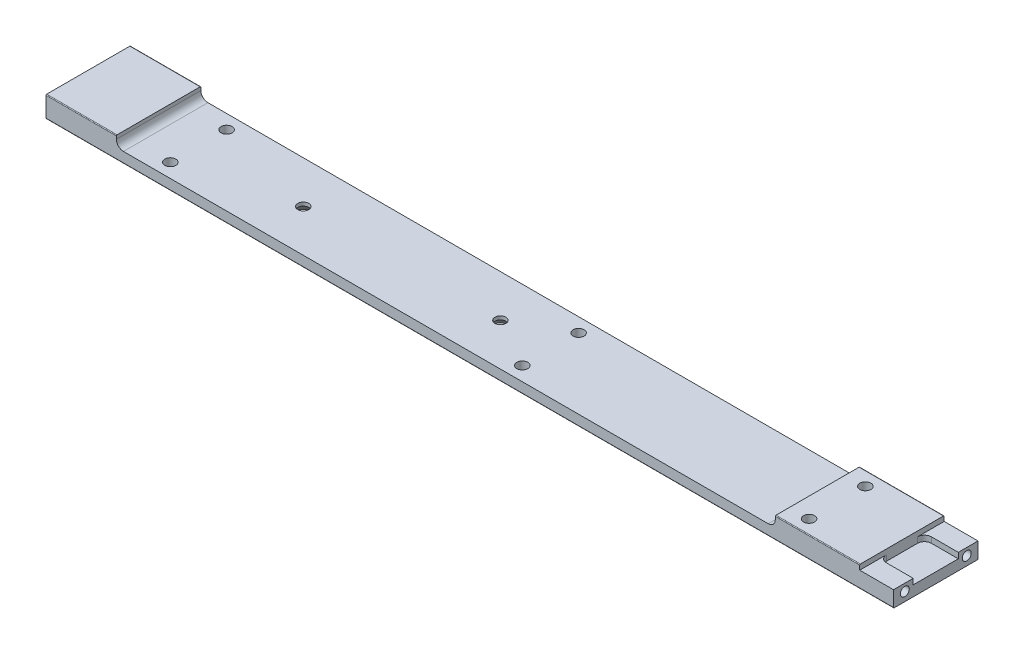
SolidWorks part; units mm, degrees
material "6061 Alloy"
ref_plane "Front Plane" through (0, 0, 0) normal (0, 0, 1) x (1, 0, 0)
ref_plane "Top Plane" through (0, 0, 0) normal (0, 1, 0) x (1, 0, 0)
ref_plane "Right Plane" through (0, 0, 0) normal (1, 0, 0) x (0, 0, -1)
sketch "Sketch1" plane through (0, 0, 0) normal (0, 1, 0) x (1, 0, 0)
  line L1 (191.135, -19.05) -> (-191.135, -19.05)
  line L2 (191.135, -19.05) -> (191.135, 19.05)
  line L3 (191.135, 19.05) -> (-191.135, 19.05)
  line L4 (-191.135, -19.05) -> (-191.135, 19.05)
  line L5 (191.135, -19.05) -> (-191.135, 19.05) construction
  line L6 (191.135, 19.05) -> (-191.135, -19.05) construction
  point P0 (0, 0)
  dimension "Length" = 382.27
  dimension "Width" = 38.1
sketch "Sketch2" plane through (0, 0, 0) normal (1, 0, 0) x (0, 0, -1)
  line L0 (19.05, 4.7625) -> (19.05, -4.7625) construction
  point P2 (19.05, 0)
  dimension "Thickness" = 9.525
sketch "Sketch3" plane through (0, 0, 0) normal (0, 1, 0) x (1, 0, 0)
  line L1 (-191.135, 19.05) -> (191.135, 19.05)
  line L2 (-191.135, 19.05) -> (-191.135, -19.05)
  line L3 (-191.135, -19.05) -> (191.135, -19.05)
  line L4 (191.135, 19.05) -> (191.135, -19.05)
extrude "Boss-Extrude1" add sketch "Sketch3" against normal up to vertex (4.7625 mm away) and the other way up to vertex (4.7625 mm away) up to point (0, -4.7625, -19.05) other way up to point (0, 4.7625, -19.05)
fillet "Fillet1" radius 0.3143 4 edges at (0, -4.7625, 19.05) (0, -4.7625, -19.05) (0, 4.7625, -19.05) (0, 4.7625, 19.05)
sketch "Sketch4" plane through (-191.135, 0, 0) normal (-1, 0, 0) x (0, 0, 1)
  line L0 (0, -0.762) -> (13.97, -0.762) construction
  line L1 (0, -0.762) -> (-13.97, -0.762) construction
  line L2 (0, -0.762) -> (0, 0) construction
  dimension "D1" = 13.97
  dimension "D2" = 13.97
  dimension "D3" = 0.762
hole_wizard "Tap Drill for #10-32 Tap1" positions "Sketch5" profile "Sketch6" hole size "#10-32" standard "ANSI Inch"
sketch "Sketch5" plane through (-191.135, 0, 0) normal (-1, 0, 0) x (0, 0, 1)
  point P0 (-13.97, -0.762)
  point P3 (13.97, -0.762)
sketch "Sketch6" plane through (-191.135, -0.762, -13.97) normal (0, 1, 0) x (0, 0, 1)
  line L0 (0, 0) -> (0, 26.6133)
  line L1 (0, 26.6133) -> (2.0193, 25.4)
  line L2 (2.0193, 25.4) -> (2.0193, 0)
  line L5 (2.0193, 0) -> (0, 0)
  line L10 (0, 26.6133) -> (-2.0193, 25.4) construction
  line L11 (0, -6.35) -> (0, 107.95) construction
  dimension "Hole Dia." = 4.0386
  dimension "Hole Depth" = 25.4
  dimension "Drill Angle" = 118
hole_wizard "Tap Drill for #10-32 Tap2" positions "Sketch7" profile "Sketch8" hole size "#10-32" standard "ANSI Inch"
sketch "Sketch7" plane through (191.135, 0, 0) normal (1, 0, 0) x (0, 0, -1)
  point P0 (-13.97, -0.762)
  point P3 (13.97, -0.762)
sketch "Sketch8" plane through (191.135, -0.762, 13.97) normal (0, 1, 0) x (0, 0, -1)
  line L0 (0, 0) -> (0, 26.6133)
  line L1 (0, 26.6133) -> (2.0193, 25.4)
  line L2 (2.0193, 25.4) -> (2.0193, 0)
  line L5 (2.0193, 0) -> (0, 0)
  line L10 (0, 26.6133) -> (-2.0193, 25.4) construction
  line L11 (0, -6.35) -> (0, 107.95) construction
  dimension "Hole Dia." = 4.0386
  dimension "Hole Depth" = 25.4
  dimension "Drill Angle" = 118
sketch "Sketch10" plane through (0, 0, -19.05) normal (0, 0, -1) x (-1, 0, 0)
  line L0 (159.385, 4.7625) -> (159.385, 3.175)
  line L1 (-191.135, 4.7625) -> (191.135, 4.7625) construction
  line L2 (156.21, 0) -> (-134.62, 0)
  line L3 (-137.795, 3.175) -> (-137.795, 4.7625)
  line L4 (-137.795, 4.7625) -> (159.385, 4.7625)
  line L5 (-191.135, -3.175) -> (-191.135, 33.0219) construction
  line L6 (191.135, -3.175) -> (191.135, 33.0219) construction
  line L7 (-191.135, 4.7625) -> (-175.895, 4.7625)
  line L8 (-175.895, 4.7625) -> (-175.895, 2.4765)
  line L9 (-175.895, 2.4765) -> (-191.135, 2.4765)
  line L10 (-191.135, -4.4482) -> (-191.135, 4.4482) construction
  line L11 (-191.135, 2.4765) -> (-191.135, 4.7625)
  arc A0 (159.385, 3.175) -> (156.21, 0) centre (156.21, 3.175) cw
  arc A1 (-134.62, 0) -> (-137.795, 3.175) centre (-134.62, 3.175) cw
  point P12 (159.385, 0)
  dimension "D4" = 3.175
  dimension "D1" = 53.34
  dimension "D2" = 31.75
  dimension "D3" = 4.7625
  dimension "D5" = 15.24
  dimension "D6" = 2.286
extrude "Cut-Extrude1" cut sketch "Sketch10" against normal through all
sketch "Sketch13" plane through (0, -4.7625, 0) normal (0, -1, 0) x (1, 0, 0)
  line L0 (191.135, 0) -> (146.685, 0) construction
  line L1 (191.135, 18.7357) -> (191.135, -18.7357) construction
  line L2 (146.685, 0) -> (146.685, 12.7) construction
  line L3 (146.685, 12.7) -> (114.935, 12.7) construction
  line L4 (114.935, 12.7) -> (114.935, -12.7) construction
  line L5 (114.935, -12.7) -> (146.685, -12.7) construction
  line L6 (146.685, -12.7) -> (146.685, 0) construction
  dimension "D1" = 44.45
  dimension "D2" = 31.75
  dimension "D3" = 31.75
hole_wizard "#10 Clearance Hole1" positions "Sketch14" profile "Sketch15" hole size "#10" standard "ANSI Inch" end condition through all
sketch "Sketch14" plane through (0, -4.7625, 0) normal (0, -1, 0) x (-1, 0, 0)
  point P3 (-146.685, 12.7)
  point P6 (-146.685, -12.7)
sketch "Sketch15" plane through (146.685, -4.7625, -12.7) normal (1, 0, 0) x (0, 0, -1)
  line L0 (0, 0) -> (0, 9.525)
  line L1 (0, 9.525) -> (2.4892, 9.525)
  line L2 (2.4892, 9.525) -> (2.4892, 3.1411)
  line L3 (2.4892, 3.1411) -> (5.2197, 0)
  line L5 (5.2197, 0) -> (0, 0)
  line L6 (-2.4892, 3.1411) -> (-5.2197, 0) construction
  line L11 (0, -6.35) -> (0, 107.95) construction
  dimension "Thru Hole Dia." = 4.9784
  dimension "Thru Hole Depth" = 9.525
  dimension "Near C'Sink Dia." = 10.4394
  dimension "Near C'Sink Angle" = 82
sketch "Sketch17" plane through (0, 2.4765, 0) normal (0, 1, 0) x (1, 0, 0)
  line L23 (191.135, 0) -> (191.135, 10.16)
  line L24 (191.135, -19.05) -> (191.135, 19.05) construction
  line L25 (191.135, 10.16) -> (179.07, 10.16)
  line L27 (175.895, 6.985) -> (175.895, -6.985)
  line L28 (179.07, -10.16) -> (191.135, -10.16)
  line L29 (191.135, -10.16) -> (191.135, 0)
  arc A0 (175.895, -6.985) -> (179.07, -10.16) centre (179.07, -6.985) ccw
  arc A1 (179.07, 10.16) -> (175.895, 6.985) centre (179.07, 6.985) ccw
  point P11 (175.895, 10.16)
  dimension "D2" = 3.175
  dimension "D1" = 15.24
extrude "Cut-Extrude2" cut sketch "Sketch17" against normal blind 2.54
sketch "Sketch18" plane through (0, 0, 0) normal (0, 1, 0) x (1, 0, 0)
  line L0 (30.0312, 19.05) -> (17.3312, 19.05) construction
  line L1 (134.62, 19.05) -> (-156.21, 19.05) construction
  line L3 (17.3312, 19.05) -> (17.3312, 12.7) construction
  line L4 (17.3312, 12.7) -> (17.3312, -12.7) construction
  line L5 (17.3312, -12.7) -> (17.3312, -19.05) construction
  line L6 (134.62, -19.05) -> (-156.21, -19.05) construction
  line L7 (17.3312, -19.05) -> (-141.4188, -19.05) construction
  line L8 (-141.4188, -19.05) -> (-141.4188, -12.7) construction
  line L9 (-141.4188, -12.7) -> (-141.4188, 12.7) construction
  line L10 (-141.4188, 12.7) -> (-141.4188, 19.05) construction
  dimension "D1" = 6.35
  dimension "D2" = 25.4
  dimension "D3" = 6.35
  dimension "D4" = 25.4
hole_wizard "#10 Clearance Hole2" positions "Sketch19" profile "Sketch20" hole size "#10" standard "ANSI Inch" end condition through all
sketch "Sketch19" plane through (0, 0, 0) normal (0, 1, 0) x (1, 0, 0)
  point P0 (-141.4188, 12.7)
  point P3 (-141.4188, -12.7)
  point P6 (17.3312, 12.7)
  point P9 (17.3312, -12.7)
sketch "Sketch20" plane through (-141.4188, 0, -12.7) normal (1, 0, 0) x (0, 0, 1)
  line L0 (0, 0) -> (0, 4.7625)
  line L1 (0, 4.7625) -> (2.4892, 4.7625)
  line L2 (2.4892, 4.7625) -> (2.4892, 0)
  line L5 (2.4892, 0) -> (0, 0)
  line L11 (0, -6.35) -> (0, 107.95) construction
  dimension "Thru Hole Dia." = 4.9784
  dimension "Thru Hole Depth" = 4.7625
sketch "Sketch21" plane through (191.135, 0, 0) normal (1, 0, 0) x (0, 0, -1)
  circle A0 centre (0, 33.0219) radius 31.7646 construction
hole_wizard "#10 (0.1935) Diameter Hole1" positions "Sketch22" profile "Sketch23" hole size "#10" standard "ANSI Inch" end condition through all
sketch "Sketch22" plane through (0, -4.7625, 0) normal (0, -1, 0) x (-1, 0, 0)
  point P0 (94.1337, 0)
  point P3 (5.2337, 0)
sketch "Sketch23" plane through (-94.1337, -4.7625, 0) normal (1, 0, 0) x (0, 0, -1)
  line L0 (0, 0) -> (0, 9.525)
  line L1 (0, 9.525) -> (2.4574, 9.525)
  line L2 (2.4574, 9.525) -> (2.4574, 3.1776)
  line L3 (2.4574, 3.1776) -> (5.2197, 0)
  line L5 (5.2197, 0) -> (0, 0)
  line L6 (-2.4574, 3.1776) -> (-5.2197, 0) construction
  line L11 (0, -6.35) -> (0, 107.95) construction
  dimension "Thru Hole Dia." = 4.9149
  dimension "Thru Hole Depth" = 9.525
  dimension "Near C'Sink Dia." = 10.4394
  dimension "Near C'Sink Angle" = 82
equation "\"D1@Fillet1\" = \"Thickness@Sketch2\" * .033"
